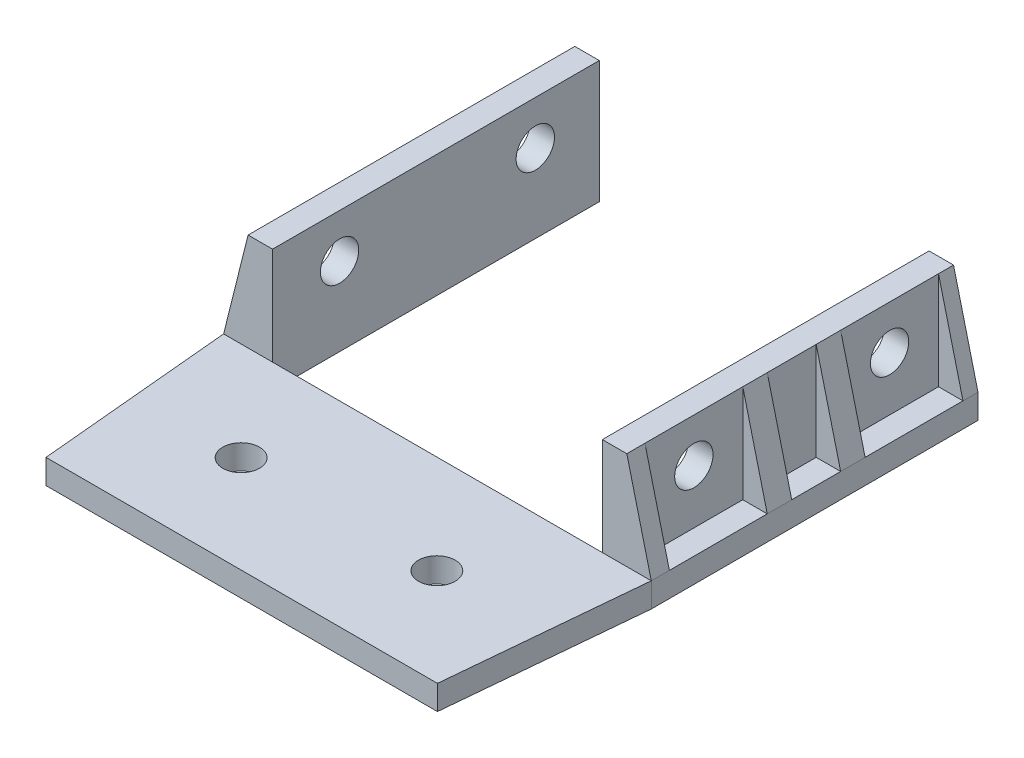
SolidWorks part; units mm, degrees
ref_plane "Front Plane" through (0, 0, 0) normal (0, 0, 1) x (1, 0, 0)
ref_plane "Top Plane" through (0, 0, 0) normal (0, 1, 0) x (1, 0, 0)
ref_plane "Right Plane" through (0, 0, 0) normal (1, 0, 0) x (0, 0, -1)
sketch "Sketch1" plane through (0, 0, 0) normal (0, 1, 0) x (1, 0, 0)
  line L0 (0.4, -0.4) -> (0.4, 42)
  line L1 (0, 0) -> (-42, 0) construction
  line L2 (0, 0) -> (0, 42) construction
  line L3 (0, 42) -> (-42, 42) construction
  line L4 (-42, 0) -> (-42, 42) construction
  line L5 (0.4, -0.4) -> (-42.4, -0.4)
  line L6 (-42.4, -0.4) -> (-42.4, 42)
  line L7 (-21, -0.4) -> (-21, -25.8) construction
  line L8 (4.4, -25.8) -> (-46.4, -25.8)
  line L9 (-42.4, 42) -> (-48.75, 42)
  line L10 (-48.75, 42) -> (-48.75, -0.4)
  line L11 (-48.75, -0.4) -> (-46.4, -25.8)
  line L12 (0.4, 42) -> (6.75, 42)
  line L13 (6.75, 42) -> (6.75, -0.4)
  line L14 (6.75, -0.4) -> (4.4, -25.8)
  point P14 (-21, -25.8)
  dimension "D1" = 42
  dimension "D2" = 42
  dimension "D4" = 25.4
  dimension "D5" = 6.35
  dimension "D6" = 50.8
  dimension "D3" = 0.4
extrude "Boss-Extrude1" add sketch "Sketch1" along normal blind 3.175
hole_wizard "3/16 (0.1875) Diameter Hole1" positions "Sketch5" profile "Sketch4" hole size "3/16" standard "ANSI Inch" end condition through all
sketch "Sketch5" plane through (0, 3.175, 0) normal (0, 1, 0) x (1, 0, 0)
  line L0 (-46.4, -25.8) -> (-46.4, -0.5563) construction
  line L1 (4.4, -25.8) -> (4.4, -0.5563) construction
  line L2 (-21, -0.4) -> (-21, -25.8) construction
  line L3 (0.4, -0.4) -> (-42.4, -0.4) construction
  line L4 (-46.4, -25.8) -> (4.4, -25.8) construction
  line L5 (-46.4, -13.1781) -> (4.4, -13.1781) construction
  point P16 (-33.7, -13.1781)
  point P18 (-8.3, -13.1781)
  dimension "D1" = 12.7
  dimension "D2" = 12.7
sketch "Sketch4" plane through (-33.7, 3.175, 13.1781) normal (1, 0, 0) x (0, 0, 1)
  line L0 (0, 0) -> (0, 3.175)
  line L1 (0, 3.175) -> (2.3812, 3.175)
  line L2 (2.3812, 3.175) -> (2.3812, 0)
  line L5 (2.3812, 0) -> (0, 0)
  line L11 (0, -6.35) -> (0, 107.95) construction
  dimension "Thru Hole Dia." = 4.7625
  dimension "Thru Hole Depth" = 3.175
sketch "Sketch6" plane through (0, 3.175, 0) normal (0, 1, 0) x (1, 0, 0)
  line L0 (-42.4, -0.4) -> (-42.4, 42) construction
  line L1 (-42.4, 14.65) -> (-45.575, 14.65)
  line L2 (-42.4, 14.65) -> (-42.4, 1.95)
  line L3 (-42.4, 1.95) -> (-45.575, 1.95)
  line L4 (-45.575, 14.65) -> (-45.575, 1.95)
  line L5 (-45.575, 8.3) -> (-42.4, 8.3) construction
  line L7 (-48.75, 20.8) -> (6.75, 20.8) construction
  line L8 (-48.75, 42) -> (-48.75, -0.4) construction
  line L9 (6.75, -0.4) -> (6.75, 42) construction
  line L10 (0.4, -0.4) -> (-42.4, -0.4) construction
  line L11 (-45.575, 33.7) -> (-42.4, 33.7) construction
  line L12 (-42.4, 40.05) -> (-45.575, 40.05)
  line L13 (-42.4, 40.05) -> (-42.4, 27.35)
  line L14 (-42.4, 27.35) -> (-45.575, 27.35)
  line L16 (-45.575, 40.05) -> (-45.575, 27.35)
  line L17 (-21, -0.4) -> (-21, -25.8) construction
  line L18 (-46.4, -25.8) -> (4.4, -25.8) construction
  line L19 (0.4, 1.95) -> (3.575, 1.95)
  line L20 (0.4, 14.65) -> (0.4, 1.95)
  line L21 (3.575, 14.65) -> (3.575, 1.95)
  line L22 (0.4, 14.65) -> (3.575, 14.65)
  line L23 (0.4, 40.05) -> (3.575, 40.05)
  line L24 (3.575, 40.05) -> (3.575, 27.35)
  line L25 (0.4, 40.05) -> (0.4, 27.35)
  line L26 (0.4, 27.35) -> (3.575, 27.35)
  dimension "D1" = 3.175
  dimension "D2" = 12.7
  dimension "D3" = 8.7
  dimension "D4" = 12.7
  dimension "D5" = 3.175
  dimension "D6" = 25.4
extrude "Boss-Extrude2" add sketch "Sketch6" along normal blind 12.7
hole_wizard "#9 (0.196) Diameter Hole1" positions "Sketch8" profile "Sketch7" hole size "#9" standard "ANSI Inch" end condition through all
sketch "Sketch8" plane through (-45.575, 0, 0) normal (-1, 0, 0) x (0, 0, 1)
  line L0 (-8.3, 3.175) -> (-8.3, 15.875) construction
  line L1 (-14.65, 3.175) -> (-1.95, 3.175) construction
  line L2 (-14.65, 15.875) -> (-1.95, 15.875) construction
  line L3 (-20.8, 3.175) -> (-20.8, 15.875) construction
  line L4 (-42, 3.175) -> (0.4, 3.175) construction
  line L5 (-33.7, 3.175) -> (-33.7, 15.875) construction
  line L6 (-40.05, 3.175) -> (-27.35, 3.175) construction
  line L7 (-40.05, 15.875) -> (-27.35, 15.875) construction
  point P8 (-8.3, 10.1854)
  point P24 (-33.7, 10.1854)
  dimension "D1" = 7.0104
sketch "Sketch7" plane through (-45.575, 10.1854, -8.3) normal (0, 1, 0) x (0, 0, 1)
  line L0 (0, 0) -> (0, 52.325)
  line L1 (0, 52.325) -> (2.4892, 52.325)
  line L2 (2.4892, 52.325) -> (2.4892, 0)
  line L5 (2.4892, 0) -> (0, 0)
  line L11 (0, -6.35) -> (0, 107.95) construction
  dimension "Thru Hole Dia." = 4.9784
  dimension "Thru Hole Depth" = 52.325
sketch "Sketch9" plane through (0, 3.175, 0) normal (0, 1, 0) x (1, 0, 0)
  line L0 (6.75, -0.4) -> (6.75, 42) construction
  line L1 (-42.4, 1.95) -> (-48.75, 1.95)
  line L2 (-42.4, 1.95) -> (-42.4, -0.4)
  line L3 (-42.4, -0.4) -> (-48.75, -0.4)
  line L4 (-48.75, 1.95) -> (-48.75, -0.4)
  line L5 (0.4, 1.95) -> (6.75, 1.95)
  line L6 (0.4, 1.95) -> (0.4, -0.4)
  line L7 (0.4, -0.4) -> (6.75, -0.4)
  line L8 (6.75, 1.95) -> (6.75, -0.4)
  line L9 (0.4, 14.65) -> (6.75, 14.65)
  line L10 (0.4, 14.65) -> (0.4, 17.825)
  line L11 (0.4, 17.825) -> (6.75, 17.825)
  line L12 (6.75, 14.65) -> (6.75, 17.825)
  line L13 (-48.75, 42) -> (-48.75, -0.4) construction
  line L14 (-42.4, 14.65) -> (-48.75, 14.65)
  line L15 (-42.4, 14.65) -> (-42.4, 17.825)
  line L16 (-42.4, 17.825) -> (-48.75, 17.825)
  line L17 (-48.75, 14.65) -> (-48.75, 17.825)
  line L18 (-42.4, 21) -> (0.4, 21) construction
  line L19 (-42.4, 14.65) -> (-42.4, 27.35) construction
  line L20 (0.4, 27.35) -> (0.4, 14.65) construction
  line L21 (0.4, 27.35) -> (0.4, 24.175)
  line L22 (0.4, 24.175) -> (6.75, 24.175)
  line L23 (0.4, 27.35) -> (6.75, 27.35)
  line L24 (6.75, 27.35) -> (6.75, 24.175)
  line L25 (6.75, 40.05) -> (6.75, 42)
  line L27 (0.4, 40.05) -> (6.75, 40.05)
  line L28 (0.4, 40.05) -> (0.4, 42)
  line L29 (-42.4, 40.05) -> (-42.4, 42)
  line L31 (-48.75, 40.05) -> (-48.75, 42)
  line L32 (-42.4, 40.05) -> (-48.75, 40.05)
  line L33 (-42.4, 27.35) -> (-42.4, 24.175)
  line L34 (-48.75, 27.35) -> (-48.75, 24.175)
  line L35 (-42.4, 24.175) -> (-48.75, 24.175)
  line L36 (-42.4, 27.35) -> (-48.75, 27.35)
  line L37 (-48.75, 42) -> (-42.4, 42)
  line L38 (0.4, 42) -> (6.75, 42)
  dimension "D1" = 3.175
  dimension "D2" = 3.175
extrude "Boss-Extrude3" add sketch "Sketch9" along normal blind 12.7
sketch "Sketch10" plane through (0, 0, 0.4) normal (0, 0, 1) x (1, 0, 0)
  line L0 (-48.75, 3.175) -> (-45.575, 15.875)
  line L1 (-48.75, 15.875) -> (-42.4, 15.875) construction
  line L2 (-45.575, 15.875) -> (-48.75, 15.875)
  line L3 (-48.75, 15.875) -> (-48.75, 3.175)
  line L4 (6.75, 3.175) -> (3.575, 15.875)
  line L5 (0.4, 15.875) -> (6.75, 15.875) construction
  line L6 (3.575, 15.875) -> (6.75, 15.875)
  line L7 (6.75, 15.875) -> (6.75, 3.175)
extrude "Cut-Extrude1" cut sketch "Sketch10" against normal through all
sketch "Sketch11" plane through (0, 3.175, 0) normal (0, 1, 0) x (1, 0, 0)
  line L0 (-48.75, 24.175) -> (-42.4, 24.175) construction
  line L1 (-45.575, 24.175) -> (-42.4, 24.175)
  line L2 (-45.575, 24.175) -> (-45.575, 17.825)
  line L3 (-45.575, 17.825) -> (-42.4, 17.825)
  line L4 (-42.4, 24.175) -> (-42.4, 17.825)
  line L5 (0.4, 24.175) -> (6.75, 24.175) construction
  line L6 (3.575, 24.175) -> (0.4, 24.175)
  line L7 (3.575, 24.175) -> (3.575, 17.825)
  line L8 (3.575, 17.825) -> (0.4, 17.825)
  line L9 (0.4, 24.175) -> (0.4, 17.825)
  line L10 (3.575, 17.825) -> (0.4, 17.825) construction
  line L11 (6.75, 17.825) -> (0.4, 17.825) construction
extrude "Boss-Extrude4" add sketch "Sketch11" along normal blind 12.7
